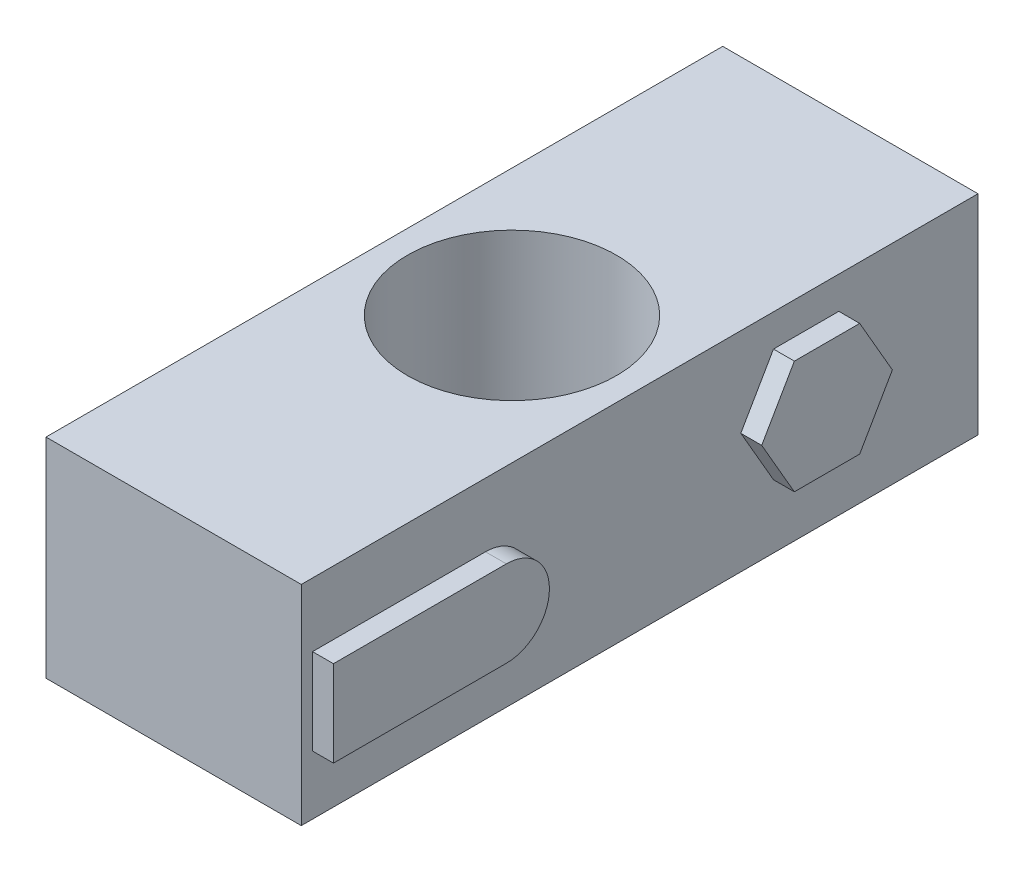
SolidWorks part; units mm, degrees
ref_plane "Front Plane" through (0, 0, 0) normal (0, 0, 1) x (1, 0, 0)
ref_plane "Top Plane" through (0, 0, 0) normal (0, 1, 0) x (1, 0, 0)
ref_plane "Right Plane" through (0, 0, 0) normal (1, 0, 0) x (0, 0, -1)
sketch "Sketch1" plane through (0, 0, 0) normal (0, 0, 1) x (1, 0, 0)
  line L0 (0, 0) -> (120, 0)
  line L1 (120, 0) -> (120, 100)
  line L2 (120, 100) -> (-180, 100)
  line L3 (-180, 100) -> (-59.7918, -20.2082)
  line L4 (-9162.1283, 1499.6244) -> (-480, 1499.6244)
  line L5 (-180, 100) -> (-480, 100)
  line L6 (-180, 100) -> (-180, 250)
  line L7 (-180, 250) -> (-480, 250)
  line L8 (-480, 100) -> (-480, 250)
  line L9 (295, -75) -> (-55, -75)
  line L10 (295, -75) -> (295, 275)
  line L11 (295, 275) -> (-55, 275)
  line L12 (-55, -75) -> (-55, 275)
  line L13 (295, -75) -> (-55, 275) construction
  line L14 (295, 275) -> (-55, -75) construction
  line L15 (-249.2317, 5.8327) -> (-133.0646, -7.0401)
  line L16 (-133.0646, -7.0401) -> (-63.8329, 87.1272)
  line L17 (-63.8329, 87.1272) -> (-110.7683, 194.1673)
  line L18 (-110.7683, 194.1673) -> (-226.9354, 207.0401)
  line L19 (-226.9354, 207.0401) -> (-296.1671, 112.8728)
  line L20 (-296.1671, 112.8728) -> (-249.2317, 5.8327)
  line L21 (-1591.3347, 432.867) -> (-1146.8962, 432.867)
  line L22 (-1611.3347, 412.867) -> (-1611.3347, 241.4995)
  line L23 (-1591.3347, 221.4995) -> (-1146.8962, 221.4995)
  line L24 (-1126.8962, 412.867) -> (-1126.8962, 241.4995)
  line L25 (-5010.3628, 1499.6244) -> (-2596.0397, 4131.9868)
  line L26 (-5010.3628, 1499.6244) -> (-7244.8716, 4131.9868)
  line L27 (-5010.3628, 1499.6244) -> (-7573.7152, -828.6606)
  line L28 (-5010.3628, 1499.6244) -> (-2781.2662, -828.6606)
  line L30 (-34130.8606, 16297.1286) -> (-21910.8606, 16297.1286)
  line L31 (-34130.8606, 16297.1286) -> (-34130.8606, 6297.1286)
  line L32 (-34130.8606, 6297.1286) -> (-21910.8606, 6297.1286)
  line L33 (-21910.8606, 16297.1286) -> (-21910.8606, 6297.1286)
  circle A0 centre (-180, 100) radius 150
  circle A1 centre (-180, 100) radius 101.2195 construction
  arc A2 (-1146.8962, 221.4995) -> (-1126.8962, 241.4995) centre (-1146.8962, 241.4995) ccw
  arc A3 (-1146.8962, 432.867) -> (-1126.8962, 412.867) centre (-1146.8962, 412.867) cw
  arc A4 (-1591.3347, 432.867) -> (-1611.3347, 412.867) centre (-1591.3347, 412.867) ccw
  arc A5 (-1611.3347, 241.4995) -> (-1591.3347, 221.4995) centre (-1591.3347, 241.4995) ccw
  arc A6 (-6120.7117, 491.098) -> (-3973.0329, 416.1362) centre (-5010.3628, 1499.6244) ccw
  arc A7 (-3996.4737, 2605.0785) -> (-5981.0788, 2643.1761) centre (-5010.3628, 1499.6244) ccw
  dimension "D6" = 300
  dimension "D7" = 20
  dimension "D8" = 10000
  dimension "D1" = 120
  dimension "D2" = 100
  dimension "D3" = 300
  dimension "D4" = 170
  dimension "D5" = 45
  dimension "D9" = 12220
extrude "Boss-Extrude2" add sketch "Sketch1" along normal blind 32393 contours L33 L30 L31 L32
sketch "Sketch2" plane through (0, 16297.1286, 0) normal (0, 1, 0) x (1, 0, 0)
  circle A0 centre (-28020.8606, -16196.5) radius 5000
  dimension "D1" = 10000
extrude "Cut-Extrude1" cut sketch "Sketch2" against normal through all
sketch "Sketch6" plane through (-21910.8606, 0, 0) normal (1, 0, 0) x (0, 0, -1)
  line L1 (-31853.088, 13241.7367) -> (-23576.0383, 13241.7367)
  line L2 (-31853.088, 13241.7367) -> (-31853.088, 9119.8324)
  line L3 (-31853.088, 9119.8324) -> (-23576.0383, 9119.8324)
  line L4 (-23576.0383, 13241.7367) -> (-23576.0383, 9119.8324)
  arc A0 (-23576.0383, 13241.7367) -> (-23576.0383, 9119.8324) centre (-23576.0383, 11180.7846) cw
extrude "Boss-Extrude3" add sketch "Sketch6" along normal blind 1000 contours L4 L1 L2 L3 | A0 L4
sketch "Sketch7" plane through (-21910.8606, 0, 0) normal (1, 0, 0) x (0, 0, -1)
  line L1 (-5098.6083, 12044.1646) -> (-6662.4122, 14752.7525)
  line L2 (-6662.4122, 14752.7525) -> (-9790.0201, 14752.7525)
  line L3 (-9790.0201, 14752.7525) -> (-11353.824, 12044.1646)
  line L4 (-11353.824, 12044.1646) -> (-9790.0201, 9335.5768)
  line L5 (-9790.0201, 9335.5768) -> (-6662.4122, 9335.5768)
  line L6 (-6662.4122, 9335.5768) -> (-5098.6083, 12044.1646)
  circle A0 centre (-8226.2162, 12044.1646) radius 2708.5878 construction
extrude "Boss-Extrude4" add sketch "Sketch7" along normal blind 1000
